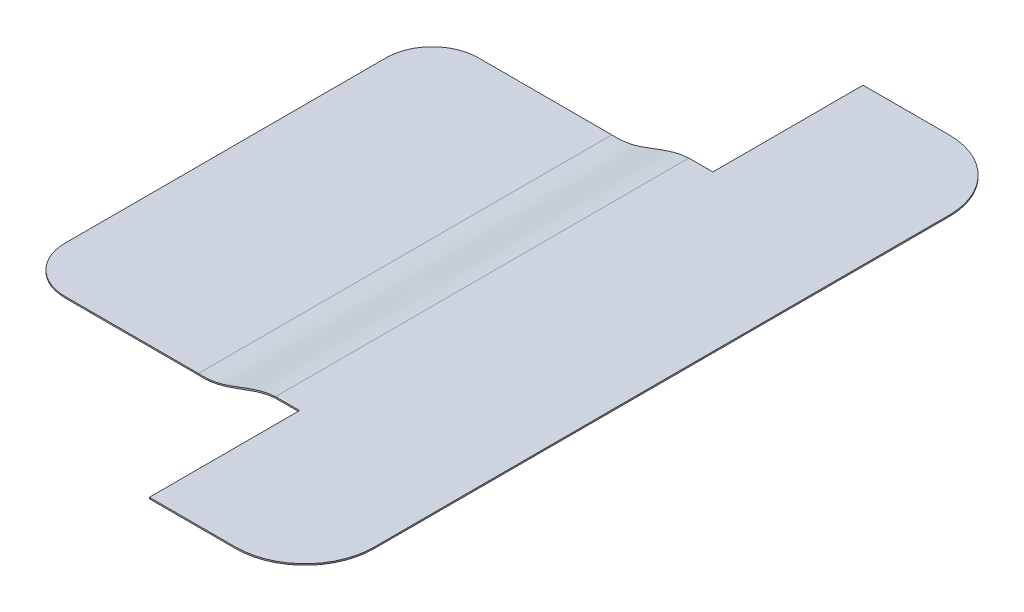
SolidWorks part; units mm, degrees
ref_plane "Front Plane" through (0, 0, 0) normal (0, 0, 1) x (1, 0, 0)
ref_plane "Top Plane" through (0, 0, 0) normal (0, 1, 0) x (1, 0, 0)
ref_plane "Right Plane" through (0, 0, 0) normal (1, 0, 0) x (0, 0, -1)
sketch "Sketch1" plane through (0, 0, 0) normal (0, 0, 1) x (1, 0, 0)
  line L0 (-1.4276, 0) -> (2.4724, 0)
  line L1 (4.1455, 0.4) -> (8.0455, 0.4)
  line L2 (-1.4276, -0.03) -> (2.4712, -0.03)
  line L3 (4.1464, 0.37) -> (8.0455, 0.37)
  line L4 (-1.4276, 0) -> (-1.4276, -0.03)
  line L5 (8.0455, 0.4) -> (8.0455, 0.37)
  spline S0 degree 3 poles (2.4724, 0) (3.0725, -0.0487) (3.5603, 0.3647) (4.1455, 0.4) knots 0 0 0 0 1 1 1 1
  spline S1 degree 1 poles (2.4712, -0.03) (4.1464, 0.37) knots 0 0 1 1 construction
  spline S2 degree 3 poles (2.4712, -0.03) (2.7605, -0.0532) (3.3388, 0.1312) (3.8627, 0.3527) (4.1464, 0.37) knots 0.000661 0.000661 0.000661 0.000661 0.500069 0.999477 0.999477 0.999477 0.999477
  dimension "D1" = 0.4
  dimension "D2" = 3.9
  dimension "D3" = 3.9
  dimension "D4" = 0.03
extrude "Boss-Extrude1" add sketch "Sketch1" along normal blind 15.5
fillet "Fillet1" radius 1.5 2 edges at (8.0455, 0.385, 15.5) (8.0455, 0.385, 0)
sketch "Sketch3" plane through (0, 0.4, 0) normal (0, 1, 0) x (1, 0, 0)
  line L0 (-9.7547, -7.75) -> (17.4299, -7.75) construction
  line L1 (-2.271, 1.4447) -> (4.6675, 1.4447)
  line L2 (-2.271, 1.4447) -> (-2.271, -3.2618)
  line L3 (-2.271, -3.2618) -> (4.6675, -3.2618)
  line L4 (4.6675, 1.4447) -> (4.6675, -3.2618)
  line L5 (4.6675, -16.9447) -> (4.6675, -12.2382)
  line L6 (-2.271, -16.9447) -> (4.6675, -16.9447)
  line L7 (-2.271, -16.9447) -> (-2.271, -12.2382)
  line L8 (-2.271, -12.2382) -> (4.6675, -12.2382)
extrude "Cut-Extrude2" cut sketch "Sketch3" against normal blind 15.5
fillet "Fillet2" radius 1 2 edges at (-1.4276, -0.015, 12.2382) (-1.4276, -0.015, 3.2618)
